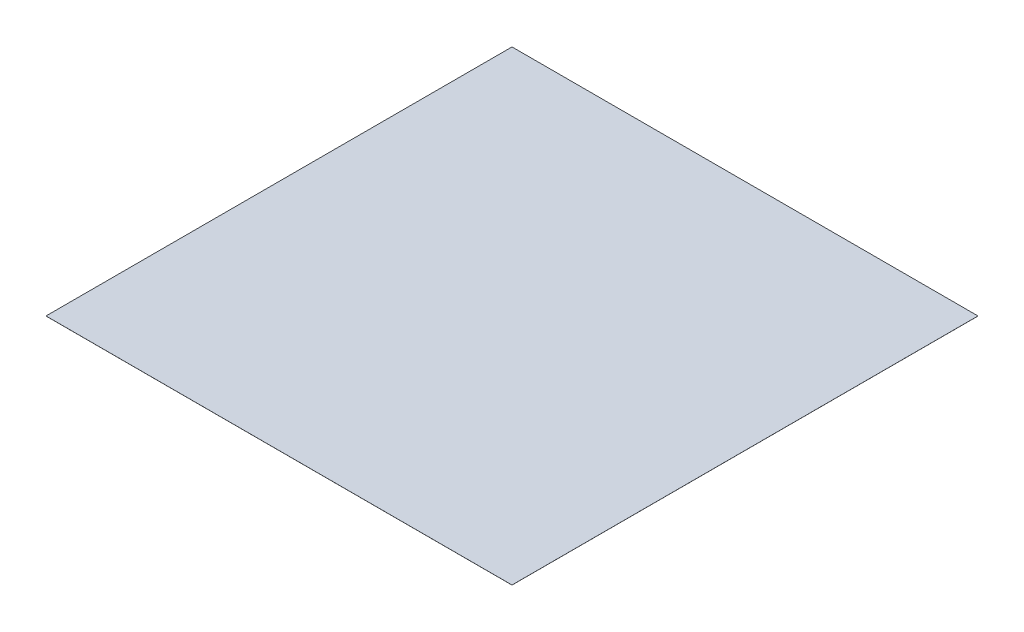
SolidWorks part; units mm, degrees
ref_plane "Front Plane" through (0, 0, 0) normal (0, 0, 1) x (1, 0, 0)
ref_plane "Top Plane" through (0, 0, 0) normal (0, 1, 0) x (1, 0, 0)
ref_plane "Right Plane" through (0, 0, 0) normal (1, 0, 0) x (0, 0, -1)
sketch "Sketch1" plane through (0, 0, 0) normal (0, 1, 0) x (1, 0, 0)
  line L1 (0, 0) -> (65, 0)
  line L2 (0, 0) -> (0, 65)
  line L3 (0, 65) -> (65, 65)
  line L4 (65, 0) -> (65, 65)
  dimension "D1" = 65
  dimension "D2" = 65
extrude "Boss-Extrude1" add sketch "Sketch1" along normal blind 0.01
sketch "Sketch2" plane through (0, 0.01, 0) normal (0, 1, 0) x (1, 0, 0)
  line L0 (32.5, 65) -> (32.5, 0)
  line L1 (65, 65) -> (0, 65) construction
  line L2 (0, 0) -> (65, 0) construction
  line L3 (0, 32.5) -> (65, 32.5)
  line L4 (0, 65) -> (0, 0) construction
  line L5 (65, 0) -> (65, 65) construction
